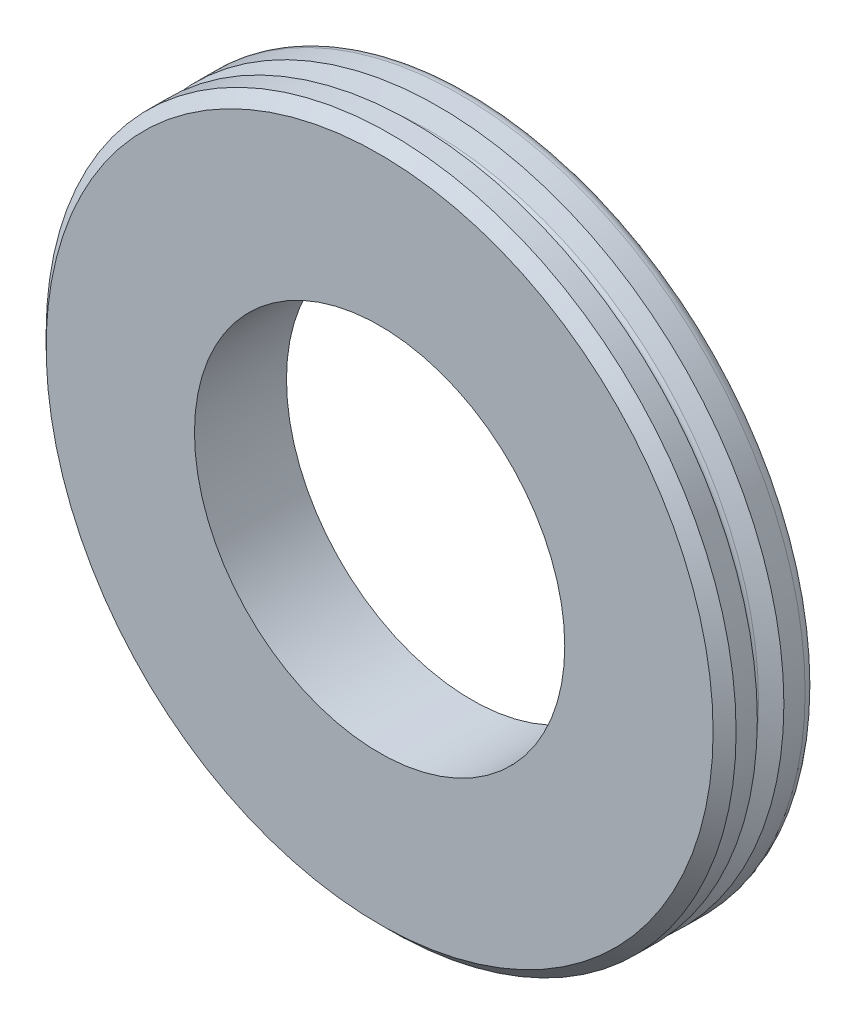
SolidWorks part; units mm, degrees
material "AISI 304"
ref_plane "Спереди" through (0, 0, 0) normal (0, 0, 1) x (1, 0, 0)
ref_plane "Сверху" through (0, 0, 0) normal (0, 1, 0) x (1, 0, 0)
ref_plane "Справа" through (0, 0, 0) normal (1, 0, 0) x (0, 0, -1)
sketch "Эскиз1" plane through (0, 0, 0) normal (0, 0, 1) x (1, 0, 0)
  circle A0 centre (0, 0) radius 15
  circle A3 centre (0, 0) radius 8.05
  dimension "D1" = 16.1
  dimension "D2" = 30
extrude "Бобышка-Вытянуть2" add sketch "Эскиз1" along normal mid plane 4
sketch "Эскиз2" plane through (0, 0, 0) normal (1, 0, 0) x (0, 0, -1)
  line L0 (-2, 15) -> (-2, -15) construction
  line L1 (-2, 15) -> (-2, -15) construction
  line L2 (-0.5774, 15) -> (0.5774, 15)
  line L3 (0.5774, 15) -> (0, 14)
  line L4 (0, 14) -> (-0.5774, 15)
  line L5 (-3.2487, 0) -> (4.3764, 0) construction
  point P5 (0, 15)
  dimension "D1" = 1
  dimension "D2" = 60
revolve "Вырез-Повернуть1" cut sketch "Эскиз2" angle 360 about L5
fillet "Скругление1" radius 0.2 1 edges at (14, 0, 0)
chamfer "Фаска1" distance 0.5 angle 45 1 edges at (15, 0, 2)
fillet "Скругление2" radius 0.5 1 edges at (15, 0, -2)
